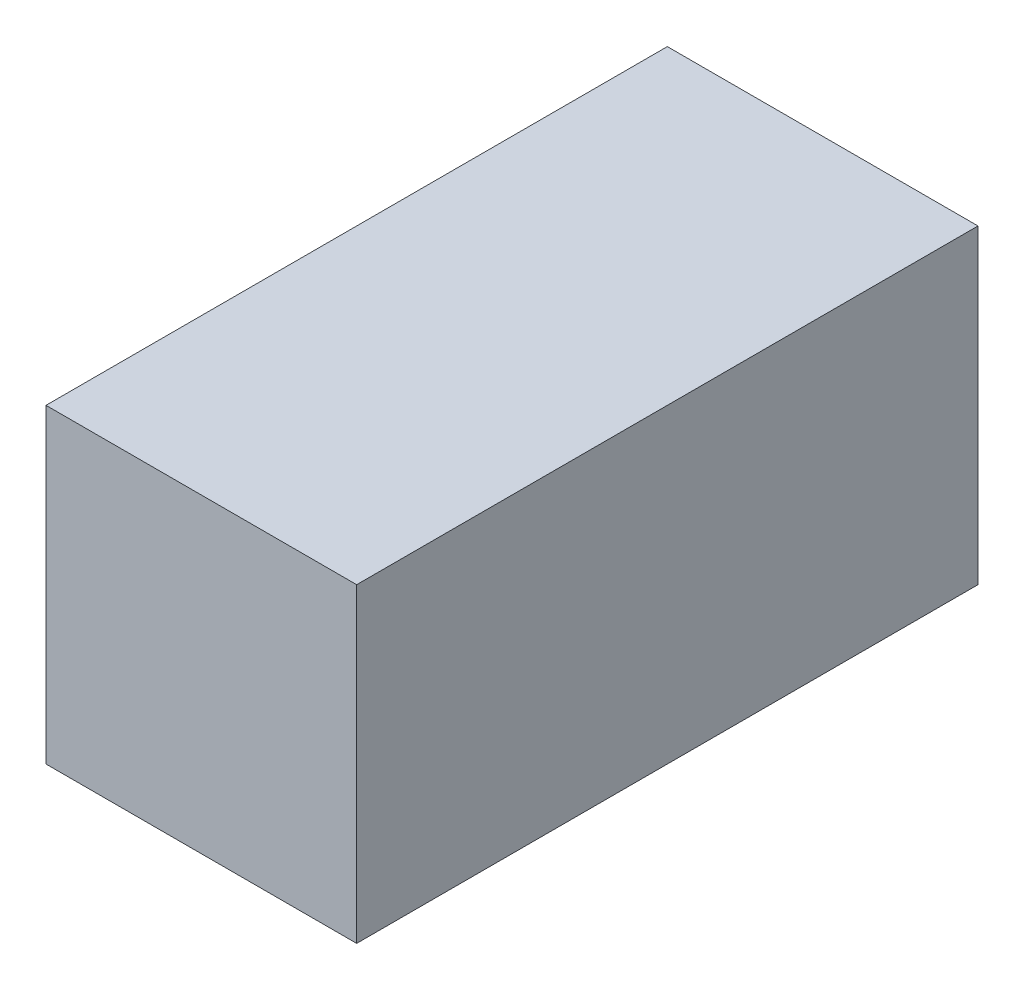
SolidWorks part; units mm, degrees
ref_plane "Front Plane" through (0, 0, 0) normal (0, 0, 1) x (1, 0, 0)
ref_plane "Top Plane" through (0, 0, 0) normal (0, 1, 0) x (1, 0, 0)
ref_plane "Right Plane" through (0, 0, 0) normal (1, 0, 0) x (0, 0, -1)
sketch "Sketch1" plane through (0, 0, 0) normal (0, 0, 1) x (1, 0, 0)
  line L1 (-17.5, 17.5) -> (17.5, 17.5)
  line L2 (-17.5, 17.5) -> (-17.5, -17.5)
  line L3 (-17.5, -17.5) -> (17.5, -17.5)
  line L4 (17.5, 17.5) -> (17.5, -17.5)
  line L5 (-17.5, 17.5) -> (17.5, -17.5) construction
  line L6 (-17.5, -17.5) -> (17.5, 17.5) construction
  point P0 (0, 0)
  dimension "D1" = 35
extrude "Boss-Extrude1" add sketch "Sketch1" along normal blind 70
